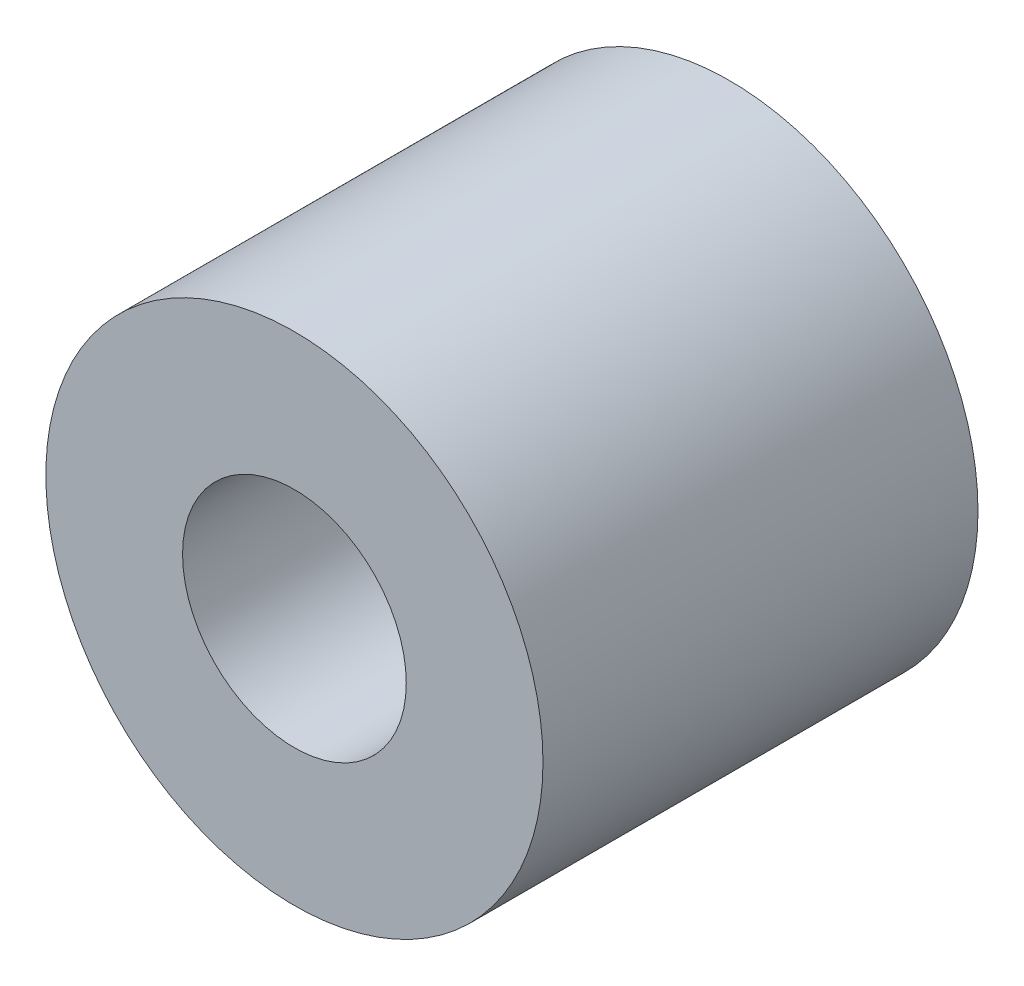
SolidWorks part; units mm, degrees
ref_plane "Front Plane" through (0, 0, 0) normal (1, 0, 0) x (0, 1, 0)
ref_plane "Top Plane" through (0, 0, 0) normal (0, 0, 1) x (0, 1, 0)
ref_plane "Right Plane" through (0, 0, 0) normal (0, 1, 0) x (-1, 0, 0)
sketch "Sketch1" plane through (0, 0, 0) normal (0, 0, 1) x (0, 1, 0)
  circle A0 centre (0, 0) radius 0.9
  circle A1 centre (0, 0) radius 2
  dimension "D1" = 1.8
  dimension "D2" = 4
extrude "Boss-Extrude1" add sketch "Sketch1" along normal blind 3.5
